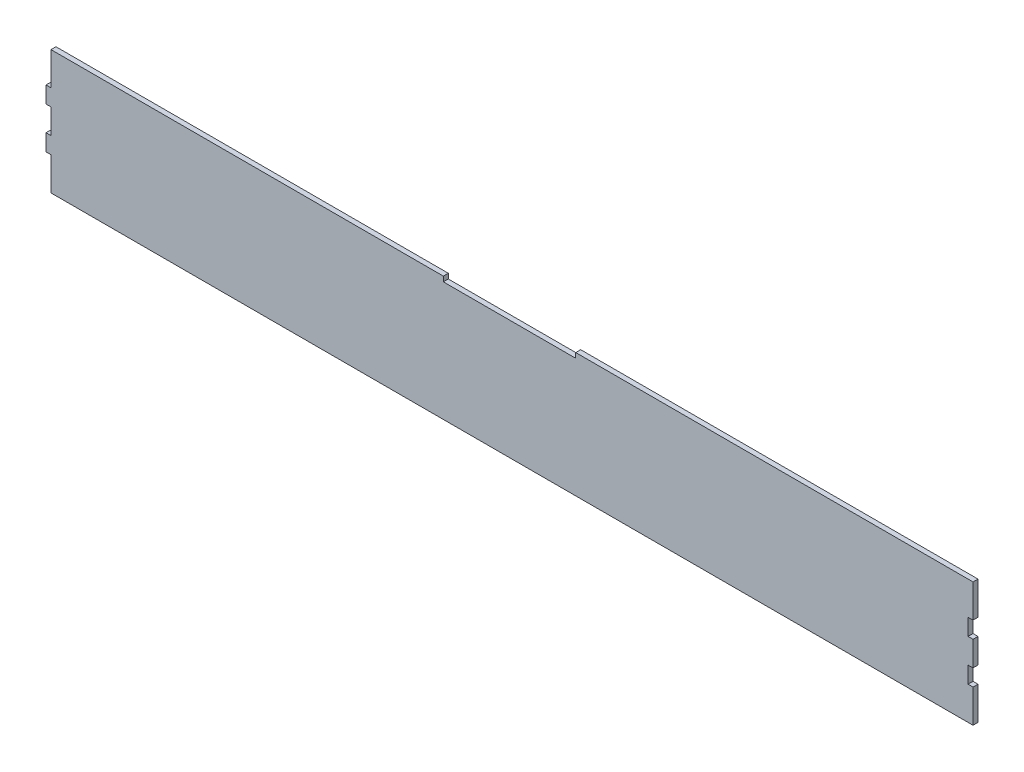
SolidWorks part; units mm, degrees
ref_plane "Front" through (0, 0, 0) normal (0, 0, 1) x (1, 0, 0)
ref_plane "Top" through (0, 0, 0) normal (0, 1, 0) x (1, 0, 0)
ref_plane "Right" through (0, 0, 0) normal (1, 0, 0) x (0, 0, -1)
sketch "Sketch1" plane through (0, 0, 0) normal (0, 0, 1) x (1, 0, 0)
  line L1 (-232.3449, 214.489) -> (327.6551, 214.489)
  line L2 (-232.3449, 214.489) -> (-232.3449, 139.489)
  line L3 (-232.3449, 139.489) -> (327.6551, 139.489)
  line L4 (327.6551, 214.489) -> (327.6551, 139.489)
  dimension "D1" = 560
  dimension "D2" = 75
extrude "Boss-Extrude1" add sketch "Sketch1" along normal blind 3 contours L2 L1 L4 L3
sketch "Sketch2" plane through (0, 0, 3) normal (0, 0, 1) x (1, 0, 0)
  line L0 (-232.3449, 214.489) -> (327.6551, 214.489) construction
  line L1 (7.6551, 214.489) -> (87.6551, 214.489)
  line L2 (7.6551, 214.489) -> (7.6551, 211.489)
  line L3 (7.6551, 211.489) -> (87.6551, 211.489)
  line L4 (87.6551, 214.489) -> (87.6551, 211.489)
  line L5 (-232.3449, 214.489) -> (-232.3449, 139.489) construction
  line L6 (327.6551, 214.489) -> (327.6551, 139.489) construction
  line L8 (327.6551, 194.489) -> (324.6551, 194.489)
  line L9 (327.6551, 194.489) -> (327.6551, 184.489)
  line L10 (327.6551, 184.489) -> (324.6551, 184.489)
  line L11 (324.6551, 194.489) -> (324.6551, 184.489)
  line L12 (327.6551, 159.489) -> (324.6551, 159.489)
  line L13 (327.6551, 159.489) -> (327.6551, 169.489)
  line L14 (327.6551, 169.489) -> (324.6551, 169.489)
  line L15 (324.6551, 159.489) -> (324.6551, 169.489)
  point P18 (326.1551, 169.489)
  dimension "D1" = 80
  dimension "D2" = 240
  dimension "D3" = 10
  dimension "D4" = 3
  dimension "D5" = 3
  dimension "D6" = 20
  dimension "D7" = 10
  dimension "D8" = 15
extrude "Cut-Extrude1" cut sketch "Sketch2" against normal blind 3 contours L9 L8 L11 L10 | L13 L12 L15 L14
sketch "Sketch3" plane through (0, 0, 3) normal (0, 0, 1) x (1, 0, 0)
  line L0 (-232.3449, 214.489) -> (-232.3449, 139.489) construction
  line L1 (-232.3449, 214.489) -> (-229.3449, 214.489)
  line L2 (-232.3449, 214.489) -> (-232.3449, 194.489)
  line L3 (-232.3449, 194.489) -> (-229.3449, 194.489)
  line L4 (-229.3449, 214.489) -> (-229.3449, 194.489)
  line L5 (-232.3449, 139.489) -> (-229.3449, 139.489)
  line L6 (-232.3449, 139.489) -> (-232.3449, 159.489)
  line L7 (-232.3449, 159.489) -> (-229.3449, 159.489)
  line L8 (-229.3449, 139.489) -> (-229.3449, 159.489)
  line L9 (-232.3449, 169.489) -> (-229.3449, 169.489)
  line L10 (-232.3449, 169.489) -> (-232.3449, 184.489)
  line L11 (-232.3449, 184.489) -> (-229.3449, 184.489)
  line L12 (-229.3449, 169.489) -> (-229.3449, 184.489)
  dimension "D1" = 20
  dimension "D2" = 3
  dimension "D3" = 3
  dimension "D4" = 15
  dimension "D5" = 10
  dimension "D6" = 3
  dimension "D7" = 20
extrude "Cut-Extrude2" cut sketch "Sketch3" against normal blind 3 contours L2 L1 L4 L3 | L10 L9 L12 L11 | L6 L5 L8 L7
sketch "Sketch4" plane through (0, 0, 3) normal (0, 0, 1) x (1, 0, 0)
  line L0 (-229.3449, 214.489) -> (327.6551, 214.489) construction
  line L1 (7.6551, 214.489) -> (87.6551, 214.489)
  line L2 (7.6551, 214.489) -> (7.6551, 211.489)
  line L3 (7.6551, 211.489) -> (87.6551, 211.489)
  line L4 (87.6551, 214.489) -> (87.6551, 211.489)
  line L5 (327.6551, 214.489) -> (327.6551, 194.489) construction
  point P6 (87.6551, 212.989)
  point P9 (47.6551, 214.489)
  dimension "D1" = 3
  dimension "D2" = 80
  dimension "D3" = 240
extrude "Cut-Extrude3" cut sketch "Sketch4" against normal blind 3 contours L2 L1 L4 L3
